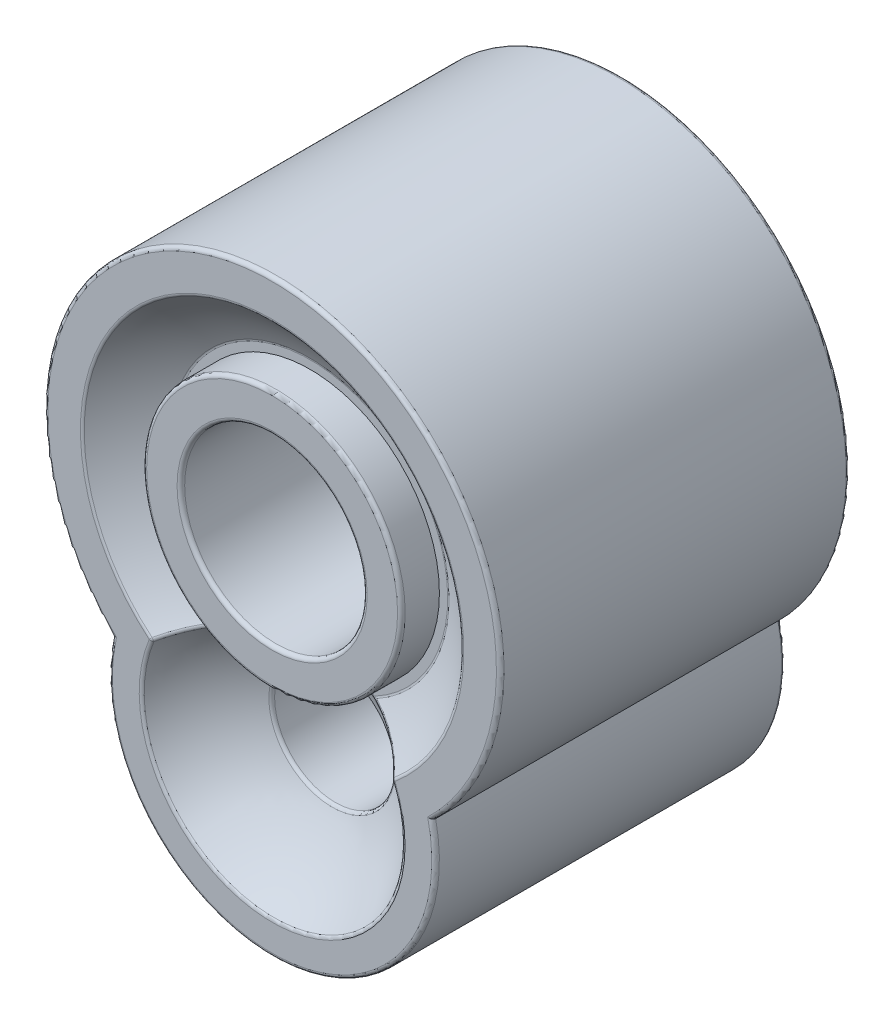
SolidWorks part; units mm, degrees
ref_plane "Front Plane" through (0, 0, 0) normal (0, 0, 1) x (1, 0, 0)
ref_plane "Top Plane" through (0, 0, 0) normal (0, 1, 0) x (1, 0, 0)
ref_plane "Right Plane" through (0, 0, 0) normal (1, 0, 0) x (0, 0, -1)
ref_plane "Plane1"
sketch "Sketch1" plane through (0, 0, 0) normal (0, 0, 1) x (1, 0, 0)
  arc A0 (4.2012, -4.2837) -> (-4.2012, -4.2837) centre (0, 0) ccw
  arc A1 (-4.2012, -4.2837) -> (4.2012, -4.2837) centre (0, -5.2) ccw
  dimension "D1" = 12
  dimension "D2" = 8.6
  dimension "D3" = 5.2
extrude "Extrusion1" add sketch "Sketch1" against normal blind 9.2
ref_plane "Plane2"
sketch "Sketch2" plane through (0, 0, 0) normal (1, 0, 0) x (0, 1, 0)
  line L0 (3.4, 0) -> (3.4, -1)
  line L1 (3.4, -1) -> (3.643, -1)
  line L2 (5, 0) -> (3.4, 0)
  line L3 (0, 0) -> (0, -8.8) construction
  line L4 (2.4, 0) -> (2.4, -1)
  line L5 (2.4, -1) -> (3.4, -1)
  line L6 (3.4, -1) -> (3.4, 0)
  line L7 (3.4, 0) -> (2.4, 0)
  line L8 (0, 0) -> (0, -8.8)
  line L9 (0, -8.8) -> (2.4, -8.8)
  line L10 (2.4, -8.8) -> (2.4, 0)
  line L11 (2.4, 0) -> (0, 0)
  arc A0 (3.643, -1) -> (5, 0) centre (1.1248, 3.8379) ccw
  dimension "D2" = 5.454
  dimension "D1" = 8.8
  dimension "D3" = 1
  dimension "D4" = 270
  dimension "D5" = 8.8
revolve "Revolution1" cut sketch "Sketch2" angle 360 about L3
ref_plane "Plane3"
sketch "Sketch3" plane through (0, 0, 0) normal (1, 0, 0) x (0, 1, 0)
  line L0 (-6.8, -1.6) -> (-6.8, 0)
  line L1 (-6.8, 0) -> (-8.64, 0)
  line L2 (-5.2, 0) -> (-5.2, -8.8) construction
  line L3 (-6.8, 0) -> (-6.8, -1.6)
  line L4 (-6.8, -1.6) -> (-6.8, -8.8)
  line L5 (-6.8, -8.8) -> (-5.2, -8.8)
  line L6 (-5.2, -8.8) -> (-5.2, 0)
  line L7 (-5.2, 0) -> (-6.8, 0)
  arc A0 (-8.64, 0) -> (-6.8, -1.6) centre (-5.2202, 2.0748) ccw
  dimension "D1" = 4
  dimension "D2" = 1.6
revolve "Revolution2" cut sketch "Sketch3" angle 360 about L2
ref_plane "Plane4"
sketch "Sketch4" plane through (0, 0, 0) normal (0, 0, 1) x (1, 0, 0)
  circle A0 centre (0, 0) radius 3.4
  circle A1 centre (0, 0) radius 2.4
  dimension "D2" = 6.8
  dimension "D3" = 4.8
  dimension "D1" = 5.2
extrude "Extrusion2" add sketch "Sketch4" against normal up to next contours A0 A1
fillet "Fillet1" radius 0.1 15 edges at (1.5664, -3.1516, -1) (-1.5664, -3.1516, -1) (2.3449, -3.4599, -0.6804) (0, 5, 0) (-2.781, -3.6515, -0.3739) (0, 3.643, -1) (2.4, 0, 0) (3.4, 0, 0) (-0.1517, -3.3966, -1.5025) (0, -8.64, 0) (1.6, -5.2, -1.6) (0, -9.5, -9.2) (0, 6, -9.2) (0, -9.5, 0) (0, 6, 0)
